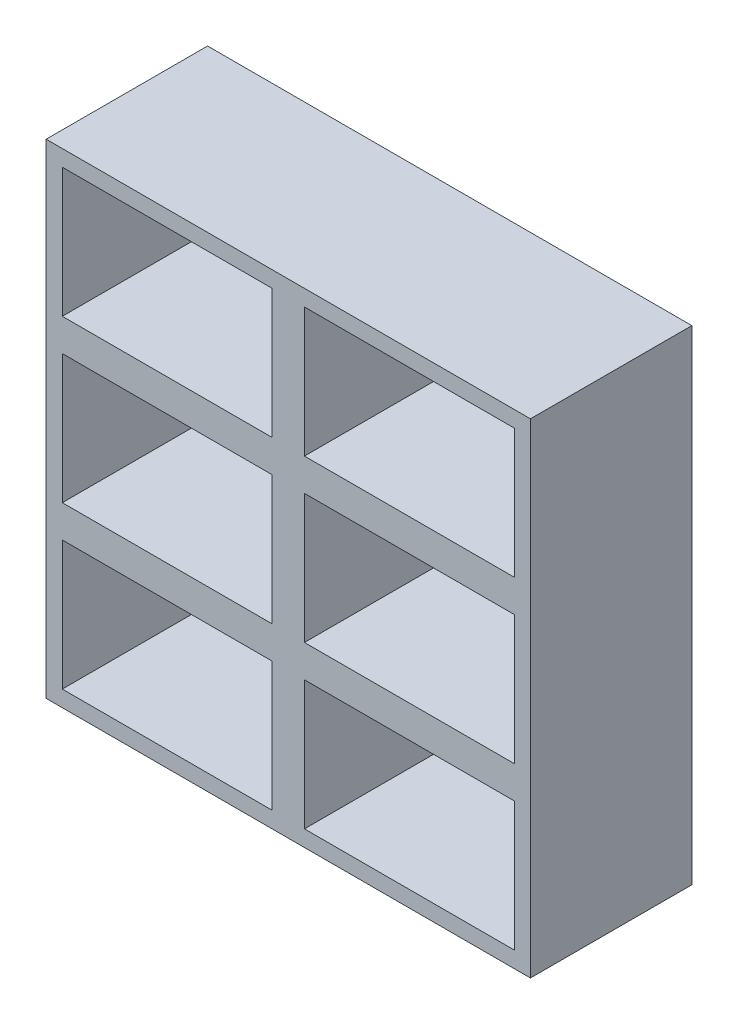
SolidWorks part; units mm, degrees
ref_plane "前视基准面" through (0, 0, 0) normal (0, 0, 1) x (1, 0, 0)
ref_plane "上视基准面" through (0, 0, 0) normal (0, 1, 0) x (1, 0, 0)
ref_plane "右视基准面" through (0, 0, 0) normal (1, 0, 0) x (0, 0, -1)
sketch "草图1" plane through (0, 0, 0) normal (0, 0, 1) x (1, 0, 0)
  line L1 (0, 0) -> (60, 0)
  line L2 (0, 0) -> (0, 60)
  line L3 (0, 60) -> (60, 60)
  line L4 (60, 0) -> (60, 60)
  dimension "D1" = 60
  dimension "D2" = 60
extrude "凸台-拉伸1" add sketch "草图1" against normal blind 20
sketch "草图2" plane through (0, 0, 0) normal (0, 0, 1) x (1, 0, 0)
  line L0 (30, 60) -> (30, 0) construction
  line L1 (60, 60) -> (0, 60) construction
  line L2 (0, 0) -> (60, 0) construction
  line L3 (0, 40) -> (60, 40) construction
  line L8 (0, 60) -> (0, 0) construction
  line L9 (60, 0) -> (60, 60) construction
  line L10 (0, 20) -> (60, 20) construction
  line L11 (30, 60) -> (30, 40) construction
  line L13 (0, 60) -> (0, 40) construction
  line L15 (2, 58) -> (2, 42)
  line L16 (2, 58) -> (28, 58)
  line L17 (28, 58) -> (28, 42)
  line L18 (28, 42) -> (2, 42)
  line L19 (30, 60) -> (60, 60) construction
  line L20 (60, 60) -> (60, 40) construction
  line L22 (0, 60) -> (30, 60) construction
  line L23 (30, 40) -> (0, 40) construction
  line L24 (30, 40) -> (60, 40) construction
  line L25 (32, 58) -> (58, 58)
  line L26 (58, 58) -> (58, 42)
  line L27 (32, 42) -> (58, 42)
  line L28 (32, 58) -> (32, 42)
  line L29 (0, 40) -> (30, 40) construction
  line L30 (30, 40) -> (30, 20) construction
  line L31 (30, 20) -> (0, 20) construction
  line L32 (0, 40) -> (0, 20) construction
  line L33 (2, 38) -> (2, 22)
  line L34 (2, 38) -> (28, 38)
  line L35 (28, 38) -> (28, 22)
  line L36 (28, 22) -> (2, 22)
  line L38 (30, 20) -> (60, 20) construction
  line L39 (60, 20) -> (60, 40) construction
  line L40 (60, 40) -> (30, 40) construction
  line L41 (58, 38) -> (32, 38)
  line L42 (32, 38) -> (32, 22)
  line L43 (32, 22) -> (58, 22)
  line L44 (58, 22) -> (58, 38)
  line L45 (30, 40) -> (30, 20) construction
  line L46 (0, 20) -> (30, 20) construction
  line L47 (0, 20) -> (0, 0) construction
  line L48 (0, 0) -> (30, 0) construction
  line L49 (30, 0) -> (30, 20) construction
  line L50 (28, 2) -> (28, 18)
  line L51 (2, 2) -> (28, 2)
  line L52 (2, 18) -> (2, 2)
  line L53 (2, 18) -> (28, 18)
  line L54 (30, 0) -> (60, 0) construction
  line L55 (60, 0) -> (60, 20) construction
  line L56 (32, 18) -> (58, 18)
  line L57 (58, 2) -> (58, 18)
  line L58 (32, 2) -> (58, 2)
  line L59 (32, 2) -> (32, 18)
  dimension "D1" = 20
  dimension "D2" = 20
  dimension "D3" = 2
  dimension "D4" = 2
  dimension "D5" = 2
  dimension "D6" = 2
  dimension "D7" = 2
  dimension "D8" = 2
extrude "切除-拉伸1" cut sketch "草图2" against normal blind 18
